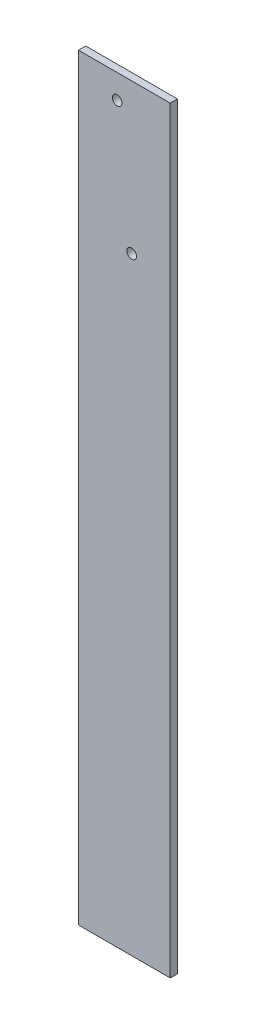
SolidWorks part; units mm, degrees
ref_plane "Plan de face" through (0, 0, 0) normal (0, 0, 1) x (1, 0, 0)
ref_plane "Plan de dessus" through (0, 0, 0) normal (0, 1, 0) x (1, 0, 0)
ref_plane "Plan de droite" through (0, 0, 0) normal (1, 0, 0) x (0, 0, -1)
sketch "Esquisse1" plane through (0, 0, 0) normal (0, 0, 1) x (1, 0, 0)
  line L0 (0, 0) -> (95, 0) construction
  line L1 (0, 0) -> (57, 0) construction
  line L2 (57, 0) -> (57, 165) construction
  line L3 (57, 165) -> (95, 165)
  line L4 (95, 165) -> (95, -149)
  line L5 (95, -149) -> (57, -149)
  line L7 (57, 165) -> (57, -149)
  dimension "D1" = 165
  dimension "D2" = 95
  dimension "D3" = 38
  dimension "D4" = 314
  dimension "D5" = 314
extrude "Boss.-Extru.1" add sketch "Esquisse1" along normal blind 3
sketch "Esquisse2" plane through (0, 0, 3) normal (0, 0, 1) x (1, 0, 0)
  line L2 (95, 165) -> (73, 165) construction
  line L3 (95, 165) -> (57, 165) construction
  line L4 (73, 165) -> (73, 155) construction
  line L5 (73, 155) -> (73, 103) construction
  line L6 (73, 103) -> (79, 103) construction
  circle A1 centre (73, 155) radius 2
  circle A2 centre (79, 103) radius 2
  dimension "D5" = 52
  dimension "D3" = 10
  dimension "D4" = 22
  dimension "D6" = 6
extrude "Enlèv. mat.-Extru.1" cut sketch "Esquisse2" against normal up to next
